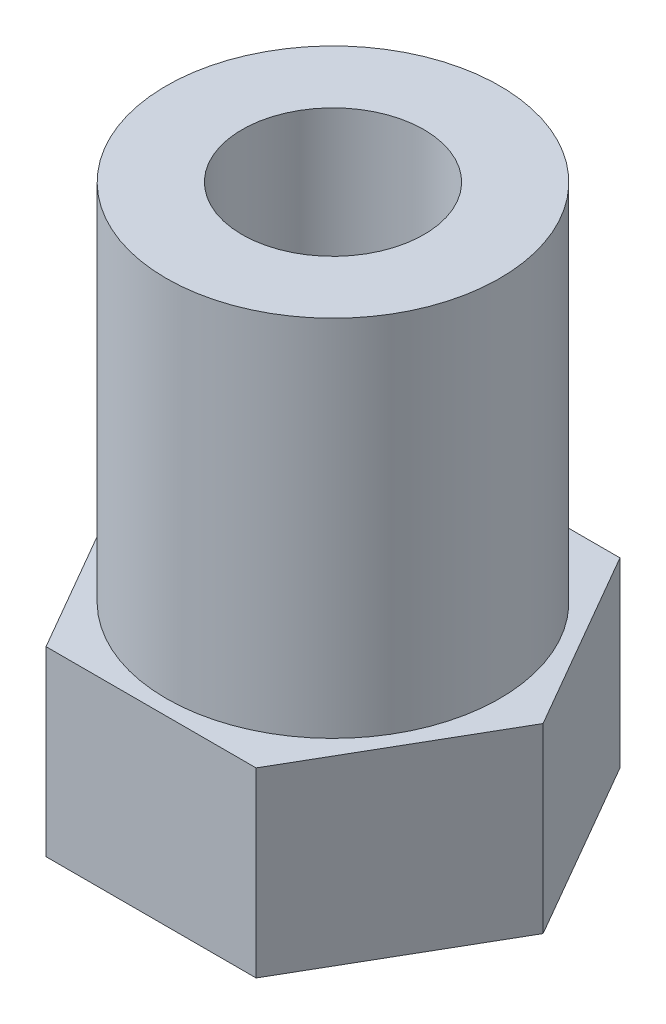
SolidWorks part; units mm, degrees
ref_plane "前视基准面" through (0, 0, 0) normal (0, 0, 1) x (1, 0, 0)
ref_plane "上视基准面" through (0, 0, 0) normal (0, 1, 0) x (1, 0, 0)
ref_plane "右视基准面" through (0, 0, 0) normal (1, 0, 0) x (0, 0, -1)
sketch "草图1" plane through (0, 0, 0) normal (0, 1, 0) x (1, 0, 0)
  line L1 (6.9282, 0) -> (3.4641, 6)
  line L2 (3.4641, 6) -> (-3.4641, 6)
  line L3 (-3.4641, 6) -> (-6.9282, 0)
  line L4 (-6.9282, 0) -> (-3.4641, -6)
  line L5 (-3.4641, -6) -> (3.4641, -6)
  line L6 (3.4641, -6) -> (6.9282, 0)
  circle A0 centre (0, 0) radius 6 construction
  circle A1 centre (0, 0) radius 3
  dimension "D1" = 12
  dimension "D2" = 6
extrude "凸台-拉伸1" add sketch "草图1" along normal blind 6
sketch "草图2" plane through (0, 6, 0) normal (0, 1, 0) x (1, 0, 0)
  circle A0 centre (0, 0) radius 5.5
  circle A1 centre (0, 0) radius 3
  dimension "D1" = 11
extrude "凸台-拉伸2" add sketch "草图2" along normal blind 12
